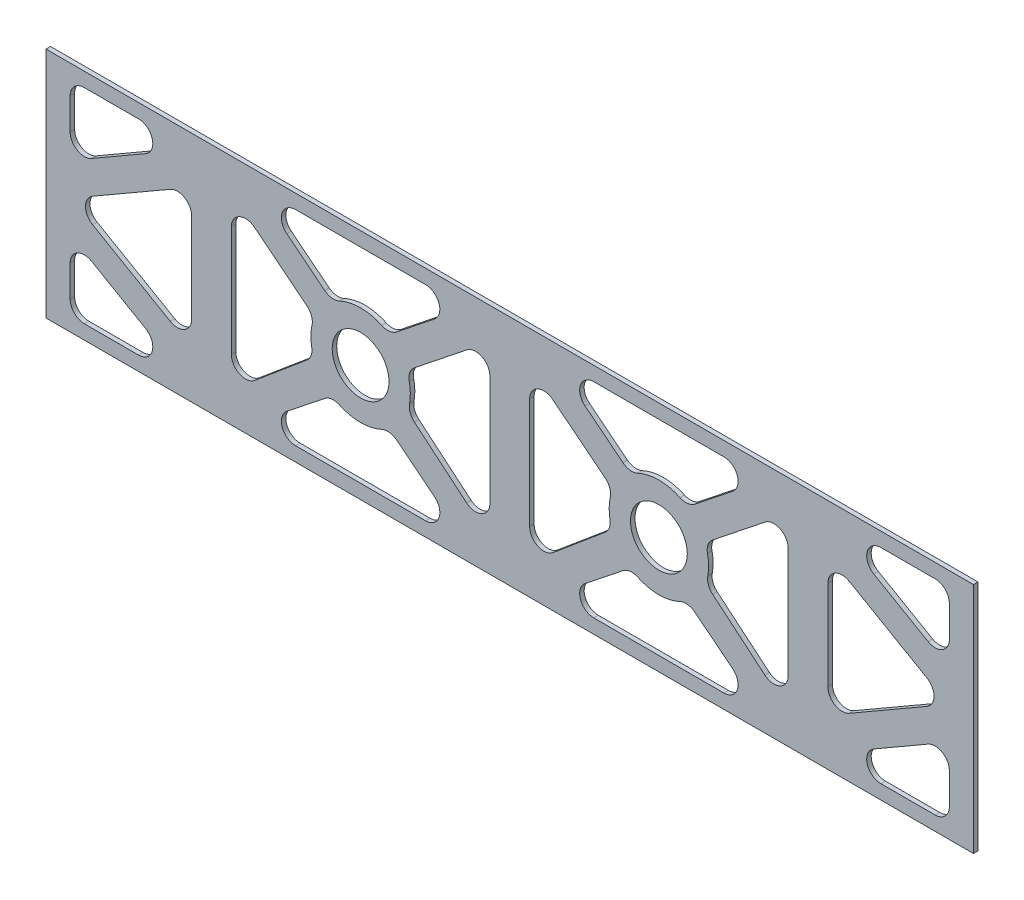
SolidWorks part; units mm, degrees
material "7075-T6, Plate (SS)"
ref_plane "Front Plane" through (0, 0, 0) normal (0, 0, 1) x (1, 0, 0)
ref_plane "Top Plane" through (0, 0, 0) normal (0, 1, 0) x (1, 0, 0)
ref_plane "Right Plane" through (0, 0, 0) normal (1, 0, 0) x (0, 0, -1)
sketch "Sketch1" plane through (0, 0, 0) normal (0, 0, 1) x (1, 0, 0)
  line L1 (0, 0) -> (326.5, 0)
  line L2 (0, 0) -> (0, -82)
  line L3 (0, -82) -> (326.5, -82)
  line L4 (326.5, 0) -> (326.5, -82)
  dimension "D1" = 82
  dimension "D2" = 326.5
extrude "Boss-Extrude1" add sketch "Sketch1" along normal blind 1.5875
sketch "Sketch2" plane through (0, 0, 1.5875) normal (0, 0, 1) x (1, 0, 0)
  line L0 (320, -89) -> (320, 7) construction
  line L1 (327, -82.5) -> (327, 0.5) construction
  line L2 (273.25, -89) -> (273.25, 7) construction
  line L3 (263.25, -89) -> (263.25, 7) construction
  line L4 (158.25, -89) -> (158.25, 7) construction
  line L5 (168.25, -89) -> (168.25, 7) construction
  line L6 (63.25, -89) -> (63.25, 7) construction
  line L7 (53.25, -89) -> (53.25, 7) construction
  line L8 (6.5, -4) -> (6.5, -78) construction
  line L9 (238.4343, -16.5548) -> (244.6618, -24.3791) construction
  line L10 (320, -89) -> (320, 7) construction
  line L11 (327, -82.5) -> (327, 0.5) construction
  line L12 (273.25, -89) -> (273.25, 7) construction
  line L13 (263.25, -89) -> (263.25, 7) construction
  line L14 (158.25, -89) -> (158.25, 7) construction
  line L15 (168.25, -89) -> (168.25, 7) construction
  line L16 (63.25, -89) -> (63.25, 7) construction
  line L17 (53.25, -89) -> (53.25, 7) construction
  line L18 (6.5, -4) -> (6.5, -78) construction
  line L19 (0, 0) -> (0, -82) construction
  line L20 (0, 0) -> (0, -82) construction
  line L21 (158.25, -41) -> (63.25, -41) construction
  line L22 (168.25, -41) -> (263.25, -41) construction
  line L23 (261.25, -21.5462) -> (261.25, -60.4538)
  line L24 (253.1363, -17.6341) -> (231.9854, -34.4684)
  line L25 (253.0361, -64.284) -> (232.2469, -46.8398)
  line L26 (192.859, -5) -> (238.641, -5)
  line L27 (241.548, -20.467) -> (215.75, -41) construction
  line L28 (225.758, -55.3559) -> (241.7547, -68.0879)
  line L29 (326.5, 0) -> (0, 0) construction
  line L30 (215.75, -41) -> (215.75, -12.5372) construction
  line L31 (225.758, -26.6441) -> (241.7547, -13.9121)
  line L32 (225.758, -55.3559) -> (205.742, -55.3559) construction
  line L33 (189.7453, -68.0879) -> (205.742, -55.3559)
  line L34 (189.7453, -13.9121) -> (205.742, -26.6441)
  line L35 (225.758, -26.6441) -> (205.742, -26.6441) construction
  line L36 (192.859, -77) -> (238.641, -77)
  line L37 (178.4639, -64.284) -> (199.2531, -46.8398)
  line L38 (170.25, -21.5462) -> (170.25, -60.4538)
  line L39 (178.3637, -17.6341) -> (199.5146, -34.4684)
  line L40 (293.9103, -5) -> (313, -5)
  line L41 (291.4103, -14.3301) -> (310.5, -25.3516)
  line L42 (318, -21.0215) -> (318, -10)
  line L43 (318, -44.1155) -> (318, -37.8845)
  line L44 (315.5, -39.7854) -> (282.75, -20.8771)
  line L45 (275.25, -25.2073) -> (275.25, -56.7927)
  line L46 (263.25, -41) -> (320, -41) construction
  line L47 (282.75, -61.1229) -> (315.5, -42.2146)
  line L48 (291.4103, -67.6699) -> (310.5, -56.6484)
  line L49 (318, -60.9785) -> (318, -72)
  line L50 (293.9103, -77) -> (313, -77)
  arc A0 (261.25, -60.4538) -> (253.0361, -64.284) centre (256.25, -60.4538) cw
  circle A1 centre (215.75, -41) radius 10
  arc A2 (261.25, -21.5462) -> (253.1363, -17.6341) centre (256.25, -21.5462) ccw
  circle A3 centre (215.75, -41) radius 17.5
  arc A4 (192.859, -5) -> (189.7453, -13.9121) centre (192.859, -10) ccw
  arc A5 (238.641, -5) -> (241.7547, -13.9121) centre (238.641, -10) cw
  arc A6 (238.641, -77) -> (241.7547, -68.0879) centre (238.641, -72) ccw
  arc A7 (192.859, -77) -> (189.7453, -68.0879) centre (192.859, -72) cw
  arc A8 (170.25, -60.4538) -> (178.4639, -64.284) centre (175.25, -60.4538) ccw
  arc A9 (170.25, -21.5462) -> (178.3637, -17.6341) centre (175.25, -21.5462) cw
  arc A10 (293.9103, -5) -> (291.4103, -14.3301) centre (293.9103, -10) ccw
  arc A11 (310.5, -56.6484) -> (318, -60.9785) centre (313, -60.9785) cw
  arc A12 (318, -72) -> (313, -77) centre (313, -72) cw
  arc A13 (291.4103, -67.6699) -> (293.9103, -77) centre (293.9103, -72) ccw
  arc A14 (275.25, -56.7927) -> (282.75, -61.1229) centre (280.25, -56.7927) ccw
  arc A15 (282.75, -20.8771) -> (275.25, -25.2073) centre (280.25, -25.2073) ccw
  arc A16 (318, -37.8845) -> (315.5, -42.2146) centre (313, -37.8845) cw
  arc A17 (318, -44.1155) -> (315.5, -39.7854) centre (313, -44.1155) ccw
  arc A18 (310.5, -25.3516) -> (318, -21.0215) centre (313, -21.0215) ccw
  arc A19 (313, -5) -> (318, -10) centre (313, -10) cw
  point P30 (261.25, -41)
  point P34 (261.25, -71.1763)
  point P37 (261.25, -11.1763)
  point P42 (215.75, -5)
  point P74 (318, -41)
  point P79 (275.25, -41)
  point P85 (275.25, -5)
  point P88 (318, -52.3183)
  point P91 (318, -77)
  point P94 (275.25, -77)
  point P105 (318, -29.6817)
  point P108 (318, -5)
  dimension "D1" = 20
  dimension "D3" = 35
  dimension "D5" = 5
  dimension "D8" = 5
  dimension "D14" = 5
  dimension "D2" = 2
  dimension "D4" = 60
  dimension "D6" = 5
  dimension "D7" = 10
  dimension "D9" = 40
  dimension "D11" = 2
  dimension "D10" = 10
  dimension "D12" = 30
  dimension "D13" = 2
extrude "Cut-Extrude1" cut sketch "Sketch2" against normal through all contours A9 L38 A8 L37 A3 L39 | A1 | A7 L36 A6 L28 A3 L33 | A3 L25 A0 L23 A2 L24 | A5 L26 A4 L34 A3 L31 | L43 A17 L44 A15 L45 A14 L47 A16 | A19 L40 A10 L41 A18 L42 | L48 A13 L50 A12 L49 A11
fillet "Fillet1" radius 5 8 edges at (205.742, -26.6441, 0.7937) (225.758, -26.6441, 0.7937) (199.2531, -46.8398, 0.7937) (199.5146, -34.4684, 0.7937) (205.742, -55.3559, 0.7937) (225.758, -55.3559, 0.7937) (232.2469, -46.8398, 0.7937) (231.9854, -34.4684, 0.7937)
fillet "Fillet2" radius 5 1 edges at (316.9107, -41, 0.7937)
ref_plane "Plane1" through (163.25, 0, 0) normal (-1, 0, 0) x (0, 0, 1)
mirror "Mirror1" about plane through (163.25, 0, 0) normal (-1, 0, 0) of "Fillet1", "Fillet2", "Cut-Extrude1"
ref_plane "Plane2" through (0, -41, 0) normal (0, -1, 0) x (-1, 0, 0)
equation "\"D11@Sketch2\"=\"D2@Sketch2\""
equation "\"D10@Sketch2\"=\"D7@Sketch2\""
equation "\"D13@Sketch2\"=\"D2@Sketch2\""
